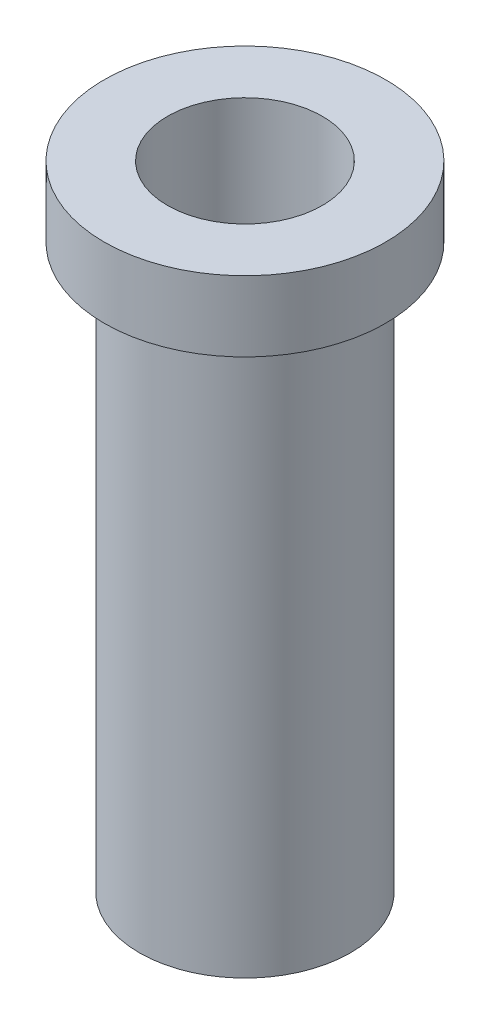
SolidWorks part; units mm, degrees
ref_plane "Front Plane" through (0, 0, 0) normal (0, 0, 1) x (1, 0, 0)
ref_plane "Top Plane" through (0, 0, 0) normal (0, 1, 0) x (1, 0, 0)
ref_plane "Right Plane" through (0, 0, 0) normal (1, 0, 0) x (0, 0, -1)
sketch "Sketch1" plane through (0, 0, 0) normal (0, 1, 0) x (1, 0, 0)
  circle A0 centre (0, 0) radius 10
  dimension "D1" = 20
extrude "Boss-Extrude1" add sketch "Sketch1" against normal blind 5
sketch "Sketch2" plane through (0, -5, 0) normal (0, -1, 0) x (1, 0, 0)
  circle A0 centre (0, 0) radius 7.5
  dimension "D1" = 15
extrude "Boss-Extrude2" add sketch "Sketch2" along normal blind 40
sketch "Sketch3" plane through (0, 0, 0) normal (0, 1, 0) x (1, 0, 0)
  circle A0 centre (0, 0) radius 5.5
  dimension "D1" = 11
extrude "Cut-Extrude1" cut sketch "Sketch3" against normal through all
